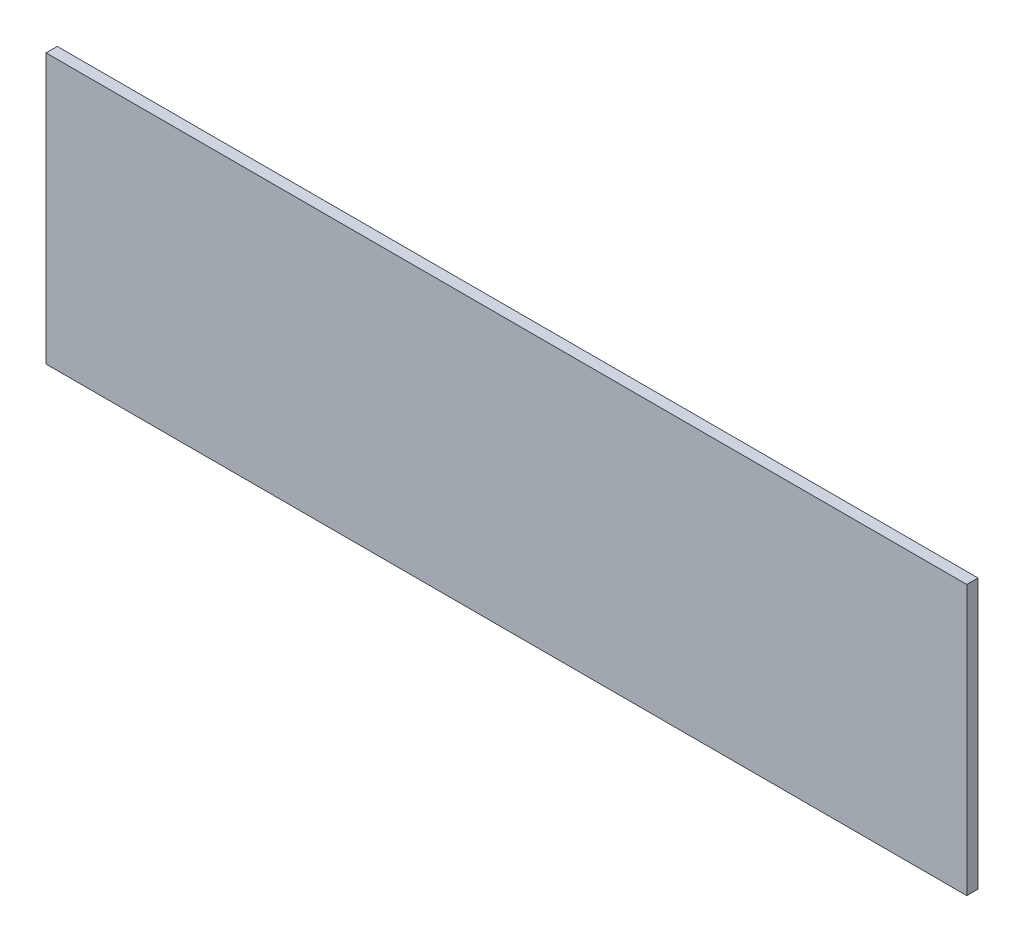
SolidWorks part; units mm, degrees
ref_plane "정면" through (0, 0, 0) normal (0, 0, 1) x (1, 0, 0)
ref_plane "윗면" through (0, 0, 0) normal (0, 1, 0) x (1, 0, 0)
ref_plane "우측면" through (0, 0, 0) normal (1, 0, 0) x (0, 0, -1)
sketch "스케치1" plane through (0, 0, 0) normal (0, 0, 1) x (1, 0, 0)
  line L1 (205, 60) -> (-205, 60)
  line L2 (205, 60) -> (205, -60)
  line L3 (205, -60) -> (-205, -60)
  line L4 (-205, 60) -> (-205, -60)
  line L5 (205, 60) -> (-205, -60) construction
  line L6 (205, -60) -> (-205, 60) construction
  point P0 (0, 0)
  dimension "D1" = 120
  dimension "D2" = 410
extrude "보스-돌출1" add sketch "스케치1" along normal blind 5
